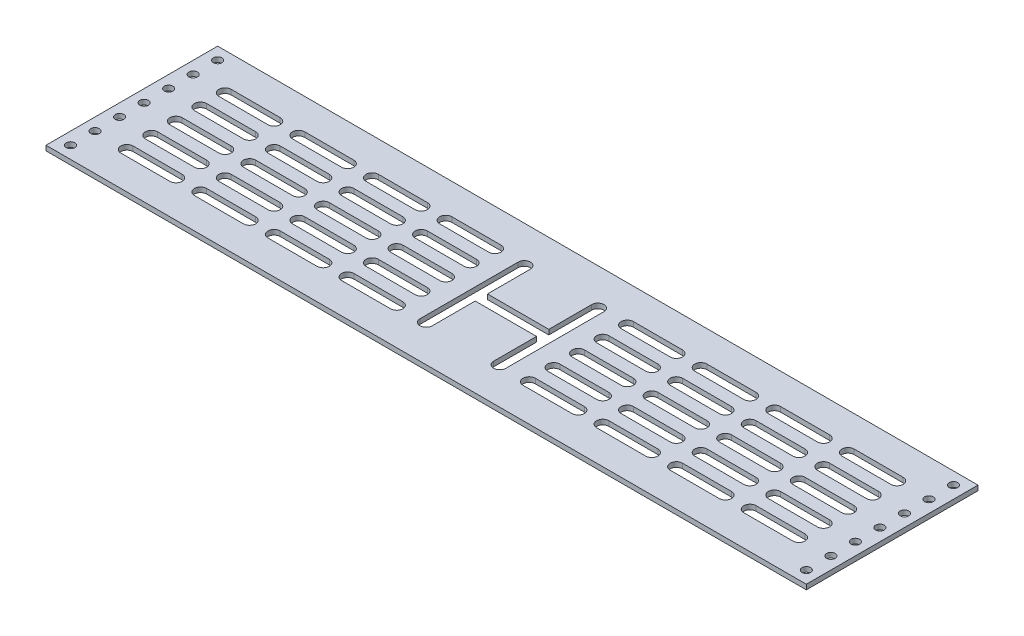
SolidWorks part; units mm, degrees
material "6061 合金"
ref_plane "前视基准面" through (0, 0, 0) normal (0, 0, 1) x (1, 0, 0)
ref_plane "上视基准面" through (0, 0, 0) normal (0, 1, 0) x (1, 0, 0)
ref_plane "右视基准面" through (0, 0, 0) normal (1, 0, 0) x (0, 0, -1)
other "Configuration Table"
sketch "草图1" plane through (0, 0, 0) normal (0, 1, 0) x (1, 0, 0)
  line L0 (0, 0) -> (-155, 0)
  line L1 (0, 0) -> (155, 0)
  line L2 (155, 0) -> (155, -80)
  line L3 (155, -80) -> (-155, -80)
  line L4 (-155, -80) -> (-155, 0)
  dimension "D1" = 155
  dimension "D2" = 80
  dimension "D3" = 155
extrude "凸台-拉伸1" add sketch "草图1" along normal blind 2
sketch "草图2" plane through (0, 2, 0) normal (0, 1, 0) x (1, 0, 0)
  line L0 (-155, -80) -> (-150, -80)
  line L1 (-155, -80) -> (155, -80) construction
  line L2 (-150, -80) -> (-150, 0)
  line L3 (155, 0) -> (-155, 0) construction
  line L4 (-150, -80) -> (-150, -75)
  line L5 (0, 0) -> (0, -80)
  circle A0 centre (-150, -75) radius 1.75
  circle A1 centre (-150, -65) radius 1.75
  circle A2 centre (-150, -55) radius 1.75
  circle A3 centre (-150, -45) radius 1.75
  circle A4 centre (-150, -35) radius 1.75
  circle A5 centre (-150, -25) radius 1.75
  circle A6 centre (-150, -15) radius 1.75
  circle A7 centre (-150, -5) radius 1.75
  circle A8 centre (150, -5) radius 1.75
  circle A9 centre (150, -15) radius 1.75
  circle A10 centre (150, -25) radius 1.75
  circle A11 centre (150, -35) radius 1.75
  circle A12 centre (150, -45) radius 1.75
  circle A13 centre (150, -55) radius 1.75
  circle A14 centre (150, -65) radius 1.75
  circle A15 centre (150, -75) radius 1.75
  dimension "D1" = 8
  dimension "D2" = 3.5
  dimension "D3" = 5
extrude "切除-拉伸1" cut sketch "草图2" against normal through all contours L4 A0 L2 | L2 A0 L4 | L2 A1 | L2 A1 | L2 A2 | L2 A2 | L2 A3 | L2 A3 | L2 A4 | L2 A4 | L2 A5 | L2 A5 | L2 A6 | L2 A6 | L2 A7 | L2 A7 | A8 | A9 | A10 | A11 | A12 | A13 | A14 | A15
sketch "草图3" plane through (0, 2, 0) normal (0, 1, 0) x (1, 0, 0)
  line L0 (0, -80) -> (0, -45)
  line L1 (155, 0) -> (-155, 0) construction
  line L2 (-155, -80) -> (155, -80) construction
  line L3 (0, -45) -> (-15, -45)
  line L4 (0, -45) -> (15, -45)
  line L5 (15, -45) -> (15, -25)
  line L6 (15, -45) -> (15, -65)
  line L7 (-15, -45) -> (-15, -25)
  line L8 (-15, -45) -> (-15, -65)
  line L9 (-15, -45) -> (15, -45) construction
  line L10 (-12.5, -42.5) -> (12.5, -42.5)
  line L11 (-12.5, -47.5) -> (12.5, -47.5)
  line L12 (-15, -25) -> (-15, -65) construction
  line L13 (-12.5, -25) -> (-12.5, -42.5)
  line L14 (-17.5, -25) -> (-17.5, -65)
  line L15 (15, -25) -> (15, -65) construction
  line L16 (17.5, -25) -> (17.5, -65)
  line L17 (12.5, -25) -> (12.5, -42.5)
  line L18 (12.5, -47.5) -> (12.5, -65)
  line L19 (-12.5, -47.5) -> (-12.5, -65)
  line L20 (-155, -80) -> (0, -80)
  line L21 (-77.5, -80) -> (-77.5, 0)
  line L22 (-150, -65) -> (-77.5, -65)
  line L25 (-147, -65) -> (-137, -65)
  line L26 (-137, -65) -> (-117, -65)
  line L27 (-117, -65) -> (-107, -65)
  line L28 (-107, -65) -> (-87, -65)
  line L29 (-87, -65) -> (-77, -65)
  line L30 (-77, -65) -> (-57, -65)
  line L34 (-137, -65) -> (-117, -65) construction
  line L35 (-137, -62.5) -> (-117, -62.5)
  line L36 (-137, -67.5) -> (-117, -67.5)
  line L37 (-107, -65) -> (-87, -65) construction
  line L38 (-107, -62.5) -> (-87, -62.5)
  line L39 (-107, -67.5) -> (-87, -67.5)
  line L40 (-77, -65) -> (-57, -65) construction
  line L41 (-77, -62.5) -> (-57, -62.5)
  line L42 (-77, -67.5) -> (-57, -67.5)
  line L45 (-137, -57.5) -> (-117, -57.5)
  line L46 (-137, -52.5) -> (-117, -52.5)
  line L47 (-107, -57.5) -> (-87, -57.5)
  line L48 (-107, -52.5) -> (-87, -52.5)
  line L49 (-77, -57.5) -> (-57, -57.5)
  line L50 (-77, -52.5) -> (-57, -52.5)
  line L52 (-137, -55) -> (-117, -55) construction
  line L53 (-107, -55) -> (-87, -55) construction
  line L54 (-77, -55) -> (-57, -55) construction
  line L57 (-137, -47.5) -> (-117, -47.5)
  line L58 (-137, -42.5) -> (-117, -42.5)
  line L59 (-107, -47.5) -> (-87, -47.5)
  line L60 (-107, -42.5) -> (-87, -42.5)
  line L61 (-77, -47.5) -> (-57, -47.5)
  line L62 (-77, -42.5) -> (-57, -42.5)
  line L64 (-137, -45) -> (-117, -45) construction
  line L65 (-107, -45) -> (-87, -45) construction
  line L66 (-77, -45) -> (-57, -45) construction
  line L69 (-137, -37.5) -> (-117, -37.5)
  line L70 (-137, -32.5) -> (-117, -32.5)
  line L71 (-107, -37.5) -> (-87, -37.5)
  line L72 (-107, -32.5) -> (-87, -32.5)
  line L73 (-77, -37.5) -> (-57, -37.5)
  line L74 (-77, -32.5) -> (-57, -32.5)
  line L76 (-137, -35) -> (-117, -35) construction
  line L77 (-107, -35) -> (-87, -35) construction
  line L78 (-77, -35) -> (-57, -35) construction
  line L99 (-147, -25) -> (-137, -25)
  line L100 (-137, -25) -> (-117, -25)
  line L101 (-117, -25) -> (-107, -25)
  line L102 (-107, -25) -> (-87, -25)
  line L109 (-87, -25) -> (-77, -25)
  line L112 (-77, -25) -> (-57, -25)
  line L115 (-57, -25) -> (-47, -25)
  line L118 (-47, -25) -> (-27, -25)
  line L178 (-137, -25) -> (-117, -25) construction
  line L181 (-57, -65) -> (-47, -65)
  line L182 (-47, -65) -> (-27, -65)
  line L183 (-47, -65) -> (-27, -65) construction
  line L184 (-47, -62.5) -> (-27, -62.5)
  line L185 (-47, -67.5) -> (-27, -67.5)
  line L186 (-47, -57.5) -> (-27, -57.5)
  line L187 (-47, -52.5) -> (-27, -52.5)
  line L188 (-47, -55) -> (-27, -55) construction
  line L189 (-47, -47.5) -> (-27, -47.5)
  line L190 (-47, -42.5) -> (-27, -42.5)
  line L191 (-47, -45) -> (-27, -45) construction
  line L192 (-47, -37.5) -> (-27, -37.5)
  line L193 (-47, -32.5) -> (-27, -32.5)
  line L194 (-47, -35) -> (-27, -35) construction
  line L197 (-137, -22.5) -> (-117, -22.5)
  line L200 (-137, -27.5) -> (-117, -27.5)
  line L202 (-107, -25) -> (-87, -25) construction
  line L205 (-107, -22.5) -> (-87, -22.5)
  line L222 (-137, -22.5) -> (-117, -22.5) [skipped]
  line L223 (-137, -27.5) -> (-117, -27.5) [skipped]
  line L224 (-107, -22.5) -> (-87, -22.5) [skipped]
  line L225 (-107, -27.5) -> (-87, -27.5) [skipped]
  line L226 (-77, -22.5) -> (-57, -22.5) [skipped]
  line L227 (-77, -27.5) -> (-57, -27.5) [skipped]
  line L230 (-137, -12.5) -> (-117, -12.5) [skipped]
  line L231 (-137, -17.5) -> (-117, -17.5) [skipped]
  line L232 (-107, -12.5) -> (-87, -12.5) [skipped]
  line L233 (-107, -17.5) -> (-87, -17.5) [skipped]
  line L234 (-77, -12.5) -> (-57, -12.5) [skipped]
  line L235 (-77, -17.5) -> (-57, -17.5) [skipped]
  line L236 (-47, -22.5) -> (-27, -22.5) [skipped]
  line L237 (-47, -27.5) -> (-27, -27.5) [skipped]
  line L238 (-47, -12.5) -> (-27, -12.5) [skipped]
  line L239 (-47, -17.5) -> (-27, -17.5) [skipped]
  line L240 (-107, -27.5) -> (-87, -27.5)
  line L241 (-77, -25) -> (-57, -25) construction
  line L242 (-77, -22.5) -> (-57, -22.5)
  line L243 (-77, -27.5) -> (-57, -27.5)
  line L244 (-47, -25) -> (-27, -25) construction
  line L245 (-47, -22.5) -> (-27, -22.5)
  line L246 (-47, -27.5) -> (-27, -27.5)
  arc A2 (-12.5, -25) -> (-17.5, -25) centre (-15, -25) ccw
  arc A3 (-17.5, -65) -> (-12.5, -65) centre (-15, -65) ccw
  arc A4 (17.5, -25) -> (12.5, -25) centre (15, -25) ccw
  arc A5 (12.5, -65) -> (17.5, -65) centre (15, -65) ccw
  arc A8 (-137, -62.5) -> (-137, -67.5) centre (-137, -65) ccw
  arc A9 (-117, -67.5) -> (-117, -62.5) centre (-117, -65) ccw
  arc A10 (-107, -62.5) -> (-107, -67.5) centre (-107, -65) ccw
  arc A11 (-87, -67.5) -> (-87, -62.5) centre (-87, -65) ccw
  arc A12 (-77, -62.5) -> (-77, -67.5) centre (-77, -65) ccw
  arc A13 (-57, -67.5) -> (-57, -62.5) centre (-57, -65) ccw
  arc A16 (-137, -52.5) -> (-137, -57.5) centre (-137, -55) ccw
  arc A17 (-117, -57.5) -> (-117, -52.5) centre (-117, -55) ccw
  arc A18 (-107, -52.5) -> (-107, -57.5) centre (-107, -55) ccw
  arc A19 (-87, -57.5) -> (-87, -52.5) centre (-87, -55) ccw
  arc A20 (-77, -52.5) -> (-77, -57.5) centre (-77, -55) ccw
  arc A21 (-57, -57.5) -> (-57, -52.5) centre (-57, -55) ccw
  arc A24 (-137, -42.5) -> (-137, -47.5) centre (-137, -45) ccw
  arc A25 (-117, -47.5) -> (-117, -42.5) centre (-117, -45) ccw
  arc A26 (-107, -42.5) -> (-107, -47.5) centre (-107, -45) ccw
  arc A27 (-87, -47.5) -> (-87, -42.5) centre (-87, -45) ccw
  arc A28 (-77, -42.5) -> (-77, -47.5) centre (-77, -45) ccw
  arc A29 (-57, -47.5) -> (-57, -42.5) centre (-57, -45) ccw
  arc A32 (-137, -32.5) -> (-137, -37.5) centre (-137, -35) ccw
  arc A33 (-117, -37.5) -> (-117, -32.5) centre (-117, -35) ccw
  arc A34 (-107, -32.5) -> (-107, -37.5) centre (-107, -35) ccw
  arc A35 (-87, -37.5) -> (-87, -32.5) centre (-87, -35) ccw
  arc A36 (-77, -32.5) -> (-77, -37.5) centre (-77, -35) ccw
  arc A37 (-57, -37.5) -> (-57, -32.5) centre (-57, -35) ccw
  arc A102 (-47, -62.5) -> (-47, -67.5) centre (-47, -65) ccw
  arc A103 (-27, -67.5) -> (-27, -62.5) centre (-27, -65) ccw
  arc A104 (-47, -52.5) -> (-47, -57.5) centre (-47, -55) ccw
  arc A105 (-27, -57.5) -> (-27, -52.5) centre (-27, -55) ccw
  arc A106 (-47, -42.5) -> (-47, -47.5) centre (-47, -45) ccw
  arc A107 (-27, -47.5) -> (-27, -42.5) centre (-27, -45) ccw
  arc A108 (-47, -32.5) -> (-47, -37.5) centre (-47, -35) ccw
  arc A109 (-27, -37.5) -> (-27, -32.5) centre (-27, -35) ccw
  arc A128 (-137, -22.5) -> (-137, -27.5) centre (-137, -25) ccw [skipped]
  arc A129 (-117, -27.5) -> (-117, -22.5) centre (-117, -25) ccw [skipped]
  arc A130 (-107, -22.5) -> (-107, -27.5) centre (-107, -25) ccw [skipped]
  arc A131 (-87, -27.5) -> (-87, -22.5) centre (-87, -25) ccw [skipped]
  arc A132 (-77, -22.5) -> (-77, -27.5) centre (-77, -25) ccw [skipped]
  arc A133 (-57, -27.5) -> (-57, -22.5) centre (-57, -25) ccw [skipped]
  arc A136 (-137, -12.5) -> (-137, -17.5) centre (-137, -15) ccw [skipped]
  arc A137 (-117, -17.5) -> (-117, -12.5) centre (-117, -15) ccw [skipped]
  arc A138 (-107, -12.5) -> (-107, -17.5) centre (-107, -15) ccw [skipped]
  arc A139 (-87, -17.5) -> (-87, -12.5) centre (-87, -15) ccw [skipped]
  arc A140 (-77, -12.5) -> (-77, -17.5) centre (-77, -15) ccw [skipped]
  arc A141 (-57, -17.5) -> (-57, -12.5) centre (-57, -15) ccw [skipped]
  arc A142 (-47, -22.5) -> (-47, -27.5) centre (-47, -25) ccw [skipped]
  arc A143 (-27, -27.5) -> (-27, -22.5) centre (-27, -25) ccw [skipped]
  arc A144 (-47, -12.5) -> (-47, -17.5) centre (-47, -15) ccw [skipped]
  arc A145 (-27, -17.5) -> (-27, -12.5) centre (-27, -15) ccw [skipped]
  arc A148 (-137, -22.5) -> (-137, -27.5) centre (-137, -25) ccw
  arc A149 (-117, -27.5) -> (-117, -22.5) centre (-117, -25) ccw
  arc A150 (-107, -22.5) -> (-107, -27.5) centre (-107, -25) ccw
  arc A151 (-87, -27.5) -> (-87, -22.5) centre (-87, -25) ccw
  arc A152 (-77, -22.5) -> (-77, -27.5) centre (-77, -25) ccw
  arc A153 (-57, -27.5) -> (-57, -22.5) centre (-57, -25) ccw
  arc A154 (-47, -22.5) -> (-47, -27.5) centre (-47, -25) ccw
  arc A155 (-27, -27.5) -> (-27, -22.5) centre (-27, -25) ccw
  point P8 (0, -40)
  point P18 (-15, -40)
  point P23 (15, -40)
  point P48 (-127, -65)
  point P53 (-97, -65)
  point P58 (-67, -65)
  point P78 (-127, -55)
  point P83 (-97, -55)
  point P88 (-67, -55)
  point P106 (-127, -45)
  point P111 (-97, -45)
  point P116 (-67, -45)
  point P134 (-127, -35)
  point P139 (-97, -35)
  point P144 (-67, -35)
  point P166 (-127, -25)
  point P171 (-97, -25)
  point P176 (-67, -25)
  point P181 (-37, -25)
  point P374 (-37, -65)
  point P383 (-37, -55)
  point P390 (-37, -45)
  point P397 (-37, -35)
  dimension "D3" = 6
  dimension "D4" = 6
  dimension "D1" = 15
  dimension "D2" = 35
  dimension "D5" = 20
  dimension "D6" = 15
  dimension "D7" = 20
sketch "草图4" plane through (0, 0, 0) normal (0, -1, 0) x (1, 0, 0)
  line L0 (150, 15) -> (150, 10)
  line L1 (150, 10) -> (187.2333, 10)
  line L2 (155, 0) -> (168.6166, 10)
  line L3 (168.6166, 10) -> (-155, 10)
  line L4 (-155, 0) -> (-155, 80) construction
  line L5 (-155, 10) -> (-155, 0)
  line L6 (-155, 0) -> (155, 0)
extrude "切除-拉伸3" cut sketch "草图4" against normal blind 10 contours L5 L6 L2 L1 L3
extrude "切除-拉伸4" cut sketch "草图3" against normal blind 10
mirror "镜向1" about plane through (0, 0, 0) normal (1, 0, 0) of "切除-拉伸4"
